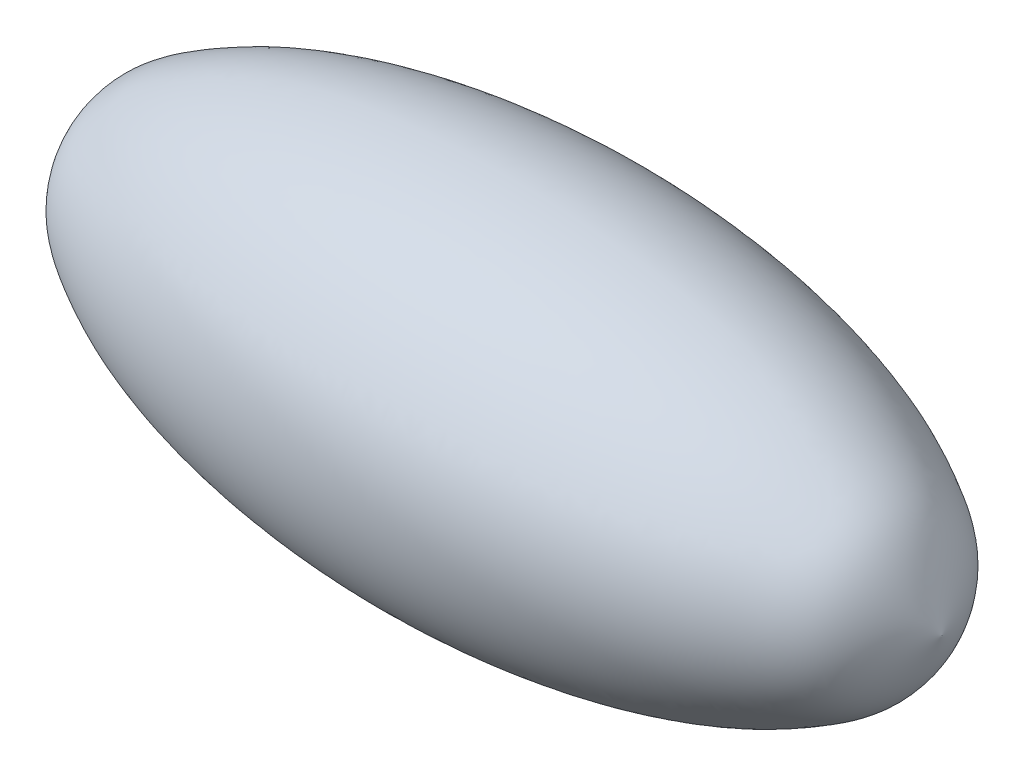
SolidWorks part; units mm, degrees
ref_plane "Front Plane" through (0, 0, 0) normal (0, 0, 1) x (1, 0, 0)
ref_plane "Top Plane" through (0, 0, 0) normal (0, 1, 0) x (1, 0, 0)
ref_plane "Right Plane" through (0, 0, 0) normal (1, 0, 0) x (0, 0, -1)
sketch "Sketch1" plane through (0, 0, 0) normal (0, 0, 1) x (1, 0, 0)
  line L0 (-260, 0) -> (0, 0)
  line L1 (10, 0) -> (-270, 0) construction
  spline S0 degree 3 poles (0, 0) (-3.3473, 8.8305) (-8.6371, 22.7855) (-25.561, 33.0216) (-38.6922, 39.4342) (-51.8523, 44.1238) (-64.8995, 47.7494) (-77.9366, 50.515) (-90.9583, 52.5666) (-103.9749, 53.9839) (-116.9881, 54.8167) (-130, 55.0915) (-143.0119, 54.8167) (-156.0251, 53.9839) (-169.0417, 52.5666) (-182.0634, 50.515) (-195.1005, 47.7494) (-208.1477, 44.1238) (-221.3078, 39.4342) (-234.439, 33.0216) (-251.3629, 22.7855) (-256.6527, 8.8305) (-260, 0) knots 0 0 0 0 0.090649 0.143253 0.191239 0.237212 0.282077 0.326262 0.370011 0.41348 0.45678 0.5 0.54322 0.58652 0.629989 0.673738 0.717923 0.762788 0.808761 0.856747 0.909351 1 1 1 1
revolve "Revolve1" add sketch "Sketch1" angle 360 about L1
